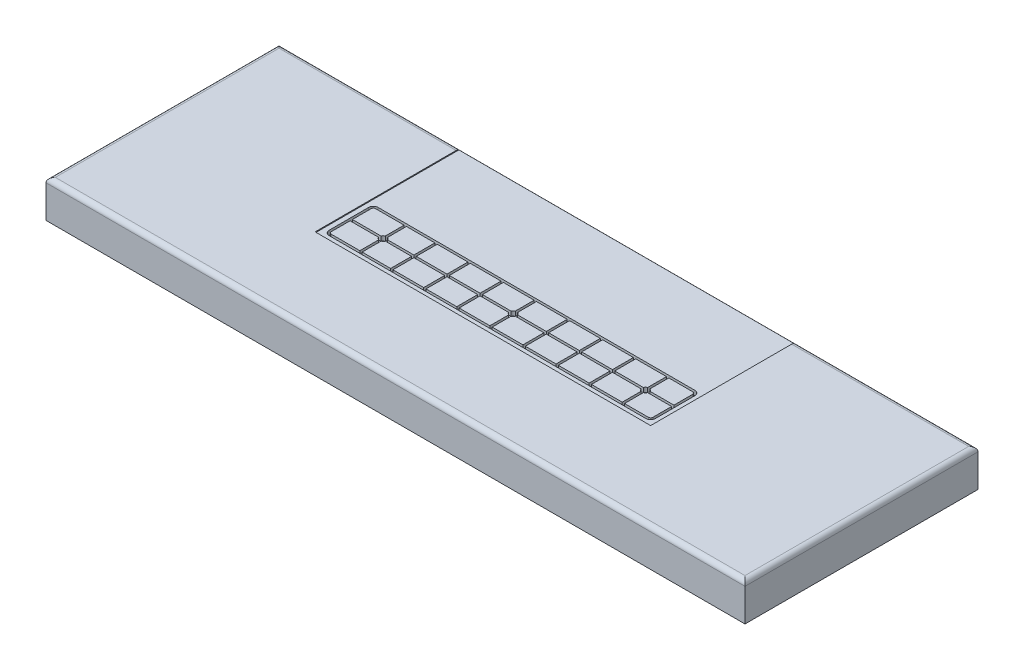
SolidWorks part; units mm, degrees
ref_plane "Front Plane" through (0, 0, 0) normal (0, 0, 1) x (1, 0, 0)
ref_plane "Top Plane" through (0, 0, 0) normal (0, 1, 0) x (1, 0, 0)
ref_plane "Right Plane" through (0, 0, 0) normal (1, 0, 0) x (0, 0, -1)
sketch "Sketch1" plane through (0, 0, 0) normal (0, 1, 0) x (1, 0, 0)
  line L1 (-750, 250) -> (750, 250)
  line L2 (-750, 250) -> (-750, -250)
  line L3 (-750, -250) -> (750, -250)
  line L4 (750, 250) -> (750, -250)
  line L5 (-750, 250) -> (750, -250) construction
  line L6 (-750, -250) -> (750, 250) construction
  point P0 (0, 0)
  dimension "D1" = 1500
  dimension "D2" = 500
extrude "Boss-Extrude1" add sketch "Sketch1" along normal blind 80
fillet "Fillet2" radius 10 4 edges at (0, 80, 250) (-750, 80, 0) (0, 80, -250) (750, 80, 0)
sketch "Sketch3" plane through (0, 0, 0) normal (0, 1, 0) x (1, 0, 0)
  line L0 (740, 148.17) -> (-740, 148.17) construction
  line L3 (-740, -148.17) -> (740, -148.17) construction
  line L4 (740, 240) -> (-740, 240) construction
  line L5 (623.2796, 240) -> (623.2796, -240) construction
  line L6 (-740, -240) -> (740, -240) construction
  dimension "D1" = 296.34
  dimension "D2" = 91.83
  dimension "D3" = 116.7204
sketch "Sketch6" plane through (0, 0, 0) normal (0, 1, 0) x (1, 0, 0)
  line L0 (623.88, 240) -> (623.88, -240) construction
  line L1 (-360, 62.5) -> (360, 62.5)
  line L2 (-360, 62.5) -> (-360, -62.5)
  line L3 (-360, -62.5) -> (360, -62.5)
  line L4 (360, 62.5) -> (360, -62.5)
  line L5 (-360, 62.5) -> (360, -62.5) construction
  line L6 (-360, -62.5) -> (360, 62.5) construction
  line L7 (740, 240) -> (-740, 240) construction
  line L8 (-740, -240) -> (740, -240) construction
  line L9 (740, -240) -> (740, 240) construction
  line L10 (-740, 148.68) -> (740, 148.68) construction
  line L11 (-740, 240) -> (-740, -240) construction
  point P0 (0, 0)
  dimension "D1" = 720
  dimension "D2" = 125
  dimension "D3" = 116.12
  dimension "D4" = 91.32
sketch "Sketch7" plane through (0, 0, 0) normal (0, 1, 0) x (1, 0, 0)
  line L1 (-661.88, 148.17) -> (473.88, 148.17) construction
  line L2 (-661.88, 148.17) -> (-661.88, -148.17) construction
  line L3 (-661.88, -148.17) -> (473.88, -148.17) construction
  line L4 (473.88, 148.17) -> (473.88, -148.17) construction
  line L5 (-661.88, 148.17) -> (473.88, -148.17) construction
  line L6 (-661.88, -148.17) -> (473.88, 148.17) construction
  line L7 (-740, 240) -> (-740, -240) construction
  line L8 (740, -240) -> (740, 240) construction
  line L9 (-661.88, 148.17) -> (-661.88, 308.5509) construction
  line L11 (473.88, 308.5509) -> (473.88, 148.17) construction
  line L12 (-360, -62.5) -> (-360, 376.5169)
  line L13 (360, -62.5) -> (360, 376.5169)
  line L14 (360, 376.5169) -> (-360, 376.5169)
  line L15 (-360, -62.5) -> (360, -62.5)
  point P8 (-94, 0)
  point P9 (-94, 0)
  point P10 (-516.2518, -356.0556)
  dimension "D1" = 78.12
  dimension "D2" = 266.12
  dimension "D3" = 296.34
extrude "Cut-Extrude2" cut sketch "Sketch7" against normal blind 2 from surface at 80 starting at face at (0, 80, 0)
sketch "Sketch5" plane through (0, 0, 0) normal (0, 1, 0) x (1, 0, 0)
  line L0 (-360, 62.5) -> (360, -62.5) construction
  line L6 (-340, 52.5) -> (340, 52.5)
  line L11 (-350, 42.5) -> (-350, -42.5)
  line L12 (-340, -52.5) -> (340, -52.5)
  line L17 (350, 42.5) -> (350, -42.5)
  line L18 (-360, 62.5) -> (-360, -62.5) construction
  line L19 (-360, -62.5) -> (360, -62.5) construction
  line L20 (360, 62.5) -> (360, -62.5) construction
  line L21 (-360, 62.5) -> (360, 62.5) construction
  line L22 (-360, -62.5) -> (360, 62.5) construction
  line L23 (-340, 47.5) -> (-279, 47.5)
  line L24 (-345, 42.5) -> (-345, 2.5)
  line L25 (-340, -47.5) -> (-279, -47.5)
  line L26 (345, 42.5) -> (345, 2.5)
  line L27 (2.5, -52.5) -> (2.5, -18.1303) construction
  line L28 (-350, 0) -> (350, 0) construction
  line L29 (-142, -2.5) -> (-142, -47.5)
  line L30 (0, 47.5) -> (0, 7.0711)
  line L31 (5, 47.5) -> (5, 7.0711)
  line L32 (-71, 47.5) -> (-71, 2.5)
  line L33 (-66, 47.5) -> (-66, 2.5)
  line L34 (142, 47.5) -> (142, 2.5)
  line L35 (147, 47.5) -> (147, 2.5)
  line L36 (71, 47.5) -> (71, 2.5)
  line L37 (76, 47.5) -> (76, 2.5)
  line L38 (213, 47.5) -> (213, 2.5)
  line L39 (218, 47.5) -> (218, 2.5)
  line L40 (284, 47.5) -> (284, 7.0711)
  line L41 (289, 47.5) -> (289, 7.0711)
  line L42 (-142, 47.5) -> (-142, 2.5)
  line L43 (-137, 47.5) -> (-137, 2.5)
  line L44 (-213, 47.5) -> (-213, 2.5)
  line L45 (-208, 47.5) -> (-208, 2.5)
  line L46 (-279, 47.5) -> (-279, 7.0711)
  line L47 (-274, 47.5) -> (-274, 7.0711)
  line L48 (-345, -2.5) -> (-283.5711, -2.5)
  line L49 (-345, 2.5) -> (-283.5711, 2.5)
  line L50 (-279, -7.0711) -> (-279, -47.5)
  line L51 (-274, -7.0711) -> (-274, -47.5)
  line L52 (-137, -2.5) -> (-71, -2.5)
  line L53 (-269.4289, -2.5) -> (-213, -2.5)
  line L54 (-269.4289, 2.5) -> (-213, 2.5)
  line L55 (-213, -2.5) -> (-213, -47.5)
  line L56 (-208, -2.5) -> (-208, -47.5)
  line L57 (-208, -2.5) -> (-142, -2.5)
  line L58 (-137, 2.5) -> (-71, 2.5)
  line L59 (-137, -2.5) -> (-137, -47.5)
  line L60 (-208, 2.5) -> (-142, 2.5)
  line L61 (-66, -2.5) -> (-4.5711, -2.5)
  line L62 (-66, 2.5) -> (-4.5711, 2.5)
  line L63 (-66, -2.5) -> (-66, -47.5)
  line L64 (-71, -2.5) -> (-71, -47.5)
  line L65 (0, -7.0711) -> (0, -47.5)
  line L66 (5, -7.0711) -> (5, -47.5)
  line L67 (9.5711, 2.5) -> (71, 2.5)
  line L68 (9.5711, -2.5) -> (71, -2.5)
  line L69 (76, -2.5) -> (142, -2.5)
  line L70 (76, -2.5) -> (76, -47.5)
  line L71 (71, -2.5) -> (71, -47.5)
  line L72 (76, 2.5) -> (142, 2.5)
  line L73 (142, -2.5) -> (142, -47.5)
  line L74 (147, -2.5) -> (147, -47.5)
  line L75 (147, -2.5) -> (213, -2.5)
  line L76 (147, 2.5) -> (213, 2.5)
  line L77 (213, -2.5) -> (213, -47.5)
  line L78 (218, -2.5) -> (218, -47.5)
  line L79 (218, 2.5) -> (279.4289, 2.5)
  line L80 (218, -2.5) -> (279.4289, -2.5)
  line L81 (284, -7.0711) -> (284, -47.5)
  line L82 (289, -7.0711) -> (289, -47.5)
  line L83 (293.5711, -2.5) -> (345, -2.5)
  line L84 (293.5711, 2.5) -> (345, 2.5)
  line L85 (345, -2.5) -> (345, -42.5)
  line L86 (-345, -2.5) -> (-345, -42.5)
  line L87 (-208, 47.5) -> (-142, 47.5)
  line L88 (-360, 84.24) -> (360, 84.24) construction
  line L89 (289, 47.5) -> (340, 47.5)
  line L90 (218, 47.5) -> (284, 47.5)
  line L91 (76, 47.5) -> (142, 47.5)
  line L92 (147, 47.5) -> (213, 47.5)
  line L93 (-66, 47.5) -> (0, 47.5)
  line L94 (5, 47.5) -> (71, 47.5)
  line L95 (-137, 47.5) -> (-71, 47.5)
  line L96 (-274, 47.5) -> (-213, 47.5)
  line L97 (-274, -47.5) -> (-213, -47.5)
  line L98 (-208, -47.5) -> (-142, -47.5)
  line L99 (-137, -47.5) -> (-71, -47.5)
  line L100 (-66, -47.5) -> (0, -47.5)
  line L101 (5, -47.5) -> (71, -47.5)
  line L102 (76, -47.5) -> (142, -47.5)
  line L103 (147, -47.5) -> (213, -47.5)
  line L104 (218, -47.5) -> (284, -47.5)
  line L105 (289, -47.5) -> (340, -47.5)
  line L106 (-279, 7.0711) -> (-274, -7.0711) construction
  line L107 (-274, 7.0711) -> (-279, -7.0711) construction
  line L108 (-360, -62.5) -> (-360, 246) construction
  line L109 (360, 246) -> (360, -62.5) construction
  line L110 (-740, 148.68) -> (740, 148.68) construction
  arc A0 (-340, -52.5) -> (-350, -42.5) centre (-340, -42.5) cw
  arc A1 (-350, 42.5) -> (-340, 52.5) centre (-340, 42.5) cw
  arc A2 (340, -52.5) -> (350, -42.5) centre (340, -42.5) ccw
  arc A3 (350, 42.5) -> (340, 52.5) centre (340, 42.5) ccw
  arc A4 (340, -47.5) -> (345, -42.5) centre (340, -42.5) ccw
  arc A5 (340, 47.5) -> (345, 42.5) centre (340, 42.5) cw
  arc A6 (-345, 42.5) -> (-340, 47.5) centre (-340, 42.5) cw
  arc A7 (-345, -42.5) -> (-340, -47.5) centre (-340, -42.5) ccw
  arc A8 (-279, 7.0711) -> (-283.5711, 2.5) centre (-276.5, 0) ccw
  arc A9 (0, 7.0711) -> (-4.5711, 2.5) centre (2.5, 0) ccw
  arc A10 (284, 7.0711) -> (279.4289, 2.5) centre (286.5, 0) ccw
  arc A11 (-283.5711, -2.5) -> (-279, -7.0711) centre (-276.5, 0) ccw
  arc A12 (-269.4289, 2.5) -> (-274, 7.0711) centre (-276.5, 0) ccw
  arc A13 (-274, -7.0711) -> (-269.4289, -2.5) centre (-276.5, 0) ccw
  arc A14 (9.5711, 2.5) -> (5, 7.0711) centre (2.5, 0) ccw
  arc A15 (-4.5711, -2.5) -> (0, -7.0711) centre (2.5, 0) ccw
  arc A16 (5, -7.0711) -> (9.5711, -2.5) centre (2.5, 0) ccw
  arc A17 (279.4289, -2.5) -> (284, -7.0711) centre (286.5, 0) ccw
  arc A18 (289, -7.0711) -> (293.5711, -2.5) centre (286.5, 0) ccw
  arc A19 (293.5711, 2.5) -> (289, 7.0711) centre (286.5, 0) ccw
  point P0 (0, 0)
  point P16 (0, 0)
  point P120 (286.5, -47.5)
  dimension "D5" = 5
  dimension "D6" = 5
  dimension "D7" = 10
  dimension "D8" = 5
  dimension "D30" = 15
  dimension "D33" = 7.5
  dimension "D34" = 15
  dimension "D1" = 10
  dimension "D2" = 10
  dimension "D3" = 10
  dimension "D4" = 10
  dimension "D9" = 5
  dimension "D10" = 5
  dimension "D11" = 5
  dimension "D12" = 5
  dimension "D13" = 5
  dimension "D14" = 5
  dimension "D15" = 5
  dimension "D16" = 5
  dimension "D17" = 66
  dimension "D18" = 66
  dimension "D19" = 66
  dimension "D20" = 5
  dimension "D21" = 66
  dimension "D22" = 66
  dimension "D23" = 66
  dimension "D24" = 66
  dimension "D25" = 66
  dimension "D26" = 66
  dimension "D27" = 2.5
  dimension "D28" = 2.5
  dimension "D29" = 5
  dimension "D31" = 2.5
  dimension "D32" = 5
  dimension "D35" = 2.5
  dimension "D36" = 64.44
extrude "Cut-Extrude1" cut sketch "Sketch5" against normal blind 10 from surface at 78 starting at face at (0, 78, -91.75)
sketch "Sketch8" plane through (0, 0, 0) normal (0, 1, 0) x (1, 0, 0)
  line L0 (284, 7.0711) -> (289, -7.0711) construction
  circle A0 centre (-276.5, 0) radius 5
  circle A1 centre (2.5, 0) radius 5
  circle A2 centre (286.5, 0) radius 5
  dimension "D1" = 10
  dimension "D2" = 10
  dimension "D3" = 10
extrude "Cut-Extrude3" cut sketch "Sketch8" against normal through all from surface at 80 starting at face at (0, 80, -44.375)
sketch "Sketch9" plane through (0, 0, 0) normal (0, 0, 1) x (1, 0, 0)
  line L0 (-740, 0) -> (740, 0) construction
  line L1 (380.9962, 0) -> (-929.3873, 0)
  line L2 (380.9962, 0) -> (380.9962, 40)
  line L3 (380.9962, 40) -> (-929.3873, 40)
  line L4 (-929.3873, 0) -> (-929.3873, 40)
  dimension "D1" = 40
extrude "Cut-Extrude4" cut sketch "Sketch9" along normal blind 100 and the other way blind 100
sketch "Sketch10" plane through (0, 0, 0) normal (0, 1, 0) x (1, 0, 0)
  line L0 (-750, -100) -> (380.9962, -100) construction
  line L2 (-162, -100) -> (-162, 100)
  line L4 (-112, -100) -> (-112, 100)
  line L5 (380.9962, 100) -> (-750, 100) construction
  line L6 (380.9962, -100) -> (-750, -100) construction
  line L8 (119.5, -100) -> (119.5, 100)
  line L10 (169.5, -100) -> (169.5, 100)
  line L11 (-750, 100) -> (380.9962, 100) construction
  line L12 (-271.5, 0) -> (-2.5, 0) construction
  line L13 (-162, -100) -> (-112, 100) construction
  line L14 (7.5, 0) -> (281.5, 0) construction
  line L15 (119.5, -100) -> (169.5, 100) construction
  line L16 (-162, -100) -> (-112, -100)
  line L17 (-162, 100) -> (-112, 100)
  line L18 (169.5, -100) -> (119.5, -100)
  line L19 (119.5, 100) -> (169.5, 100)
  line L20 (-281.5, 0) -> (-550.5, 0) construction
  line L22 (-441, 100) -> (-391, 100)
  line L23 (-441, 100) -> (-441, -100)
  line L24 (-441, -100) -> (-391, -100)
  line L25 (-391, 100) -> (-391, -100)
  line L26 (-441, 100) -> (-391, -100) construction
  line L27 (-441, -100) -> (-391, 100) construction
  circle A0 centre (-276.5, 0) radius 5 construction
  circle A1 centre (2.5, 0) radius 5 construction
  circle A2 centre (286.5, 0) radius 5 construction
  point P23 (-137, 0)
  point P24 (-137, 0)
  point P29 (144.5, 0)
  point P32 (-416, 0)
  point P34 (-416, 0)
  dimension "D1" = 50
  dimension "D2" = 50
  dimension "D3" = 269
  dimension "D4" = 50
extrude "Boss-Extrude2" add sketch "Sketch10" against normal up to surface (40 mm away) from surface at 40 up to face at (-92.2509, 0, 0) starting at face at (-2.5, 40, 0)
